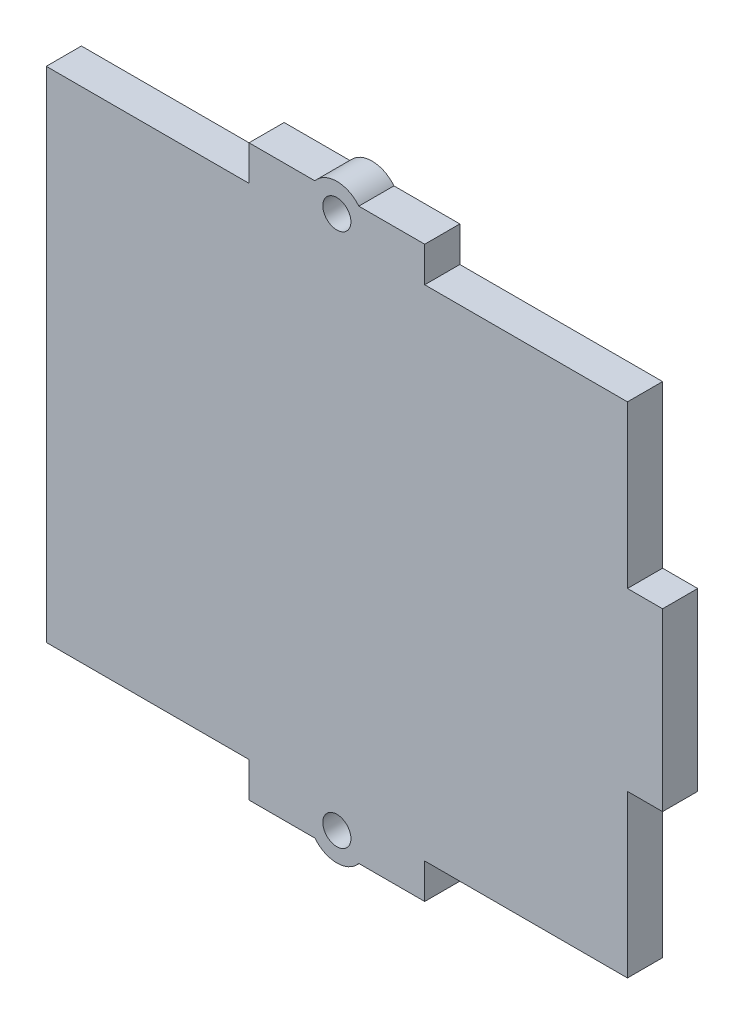
SolidWorks part; units mm, degrees
ref_plane "Front Plane" through (0, 0, 0) normal (0, 0, 1) x (1, 0, 0)
ref_plane "Top Plane" through (0, 0, 0) normal (0, 1, 0) x (1, 0, 0)
ref_plane "Right Plane" through (0, 0, 0) normal (1, 0, 0) x (0, 0, -1)
sketch "Sketch1" plane through (0, 0, 0) normal (0, 0, 1) x (1, 0, 0)
  line L1 (-41.35, 35.5) -> (41.35, 35.5)
  line L2 (-41.35, 35.5) -> (-41.35, -35.5)
  line L3 (-41.35, -35.5) -> (41.35, -35.5)
  line L4 (41.35, 35.5) -> (41.35, -35.5)
  dimension "D1" = 82.7
  dimension "D2" = 71
  dimension "D3" = 41.35
  dimension "D4" = 35.5
extrude "Boss-Extrude1" add sketch "Sketch1" along normal blind 5
sketch "Sketch3" plane through (0, 0, 5) normal (0, 0, 1) x (1, 0, 0)
  line L0 (41.35, 35.5) -> (-41.35, 35.5) construction
  line L1 (-12.5, 35.5) -> (12.5, 35.5)
  line L2 (-12.5, 35.5) -> (-12.5, 40.5)
  line L3 (-12.5, 40.5) -> (12.5, 40.5)
  line L4 (12.5, 35.5) -> (12.5, 40.5)
  line L5 (-41.35, 35.5) -> (-41.35, -35.5) construction
  line L6 (41.35, 12.5) -> (46.35, 12.5)
  line L7 (41.35, -35.5) -> (41.35, 35.5) construction
  line L8 (46.35, 12.5) -> (46.35, -12.5)
  line L9 (46.35, -12.5) -> (41.35, -12.5)
  line L10 (41.35, -12.5) -> (41.35, 12.5)
  line L11 (-41.35, -35.5) -> (41.35, -35.5) construction
  line L12 (-41.35, -35.5) -> (41.35, -35.5) construction
  line L13 (12.5, -35.5) -> (-12.5, -35.5)
  line L14 (12.5, -35.5) -> (12.5, -40.5)
  line L15 (12.5, -40.5) -> (-12.5, -40.5)
  line L16 (-12.5, -35.5) -> (-12.5, -40.5)
  dimension "D1" = 5
  dimension "D2" = 28.85
  dimension "D3" = 25
  dimension "D4" = 5
  dimension "D5" = 25
  dimension "D6" = 23
  dimension "D7" = 5
extrude "Boss-Extrude2" add sketch "Sketch3" against normal blind 5
sketch "Sketch4" plane through (0, 0, 5) normal (0, 0, 1) x (1, 0, 0)
  line L0 (12.5, 40.5) -> (-12.5, 40.5) construction
  line L1 (-12.5, -40.5) -> (12.5, -40.5) construction
  line L2 (-12.5, 40.5) -> (-12.5, 35.5) construction
  line L3 (-12.5, -35.5) -> (-12.5, -40.5) construction
  circle A0 centre (0, 38) radius 2
  circle A1 centre (0, -38) radius 2
  dimension "D1" = 4
  dimension "D2" = 4
  dimension "D3" = 2.5
  dimension "D4" = 2.5
  dimension "D5" = 12.5
  dimension "D6" = 12.5
extrude "Cut-Extrude1" cut sketch "Sketch4" against normal blind 5
sketch "Sketch5" plane through (0, 0, 5) normal (0, 0, 1) x (1, 0, 0)
  circle A0 centre (0, 38) radius 2
  circle A1 centre (0, 38) radius 4
  circle A2 centre (0, -38) radius 2
  circle A3 centre (0, -38) radius 4
  dimension "D1" = 8
  dimension "D2" = 8
  dimension "D3" = 4
  dimension "D4" = 4
extrude "Boss-Extrude3" add sketch "Sketch5" against normal blind 5
